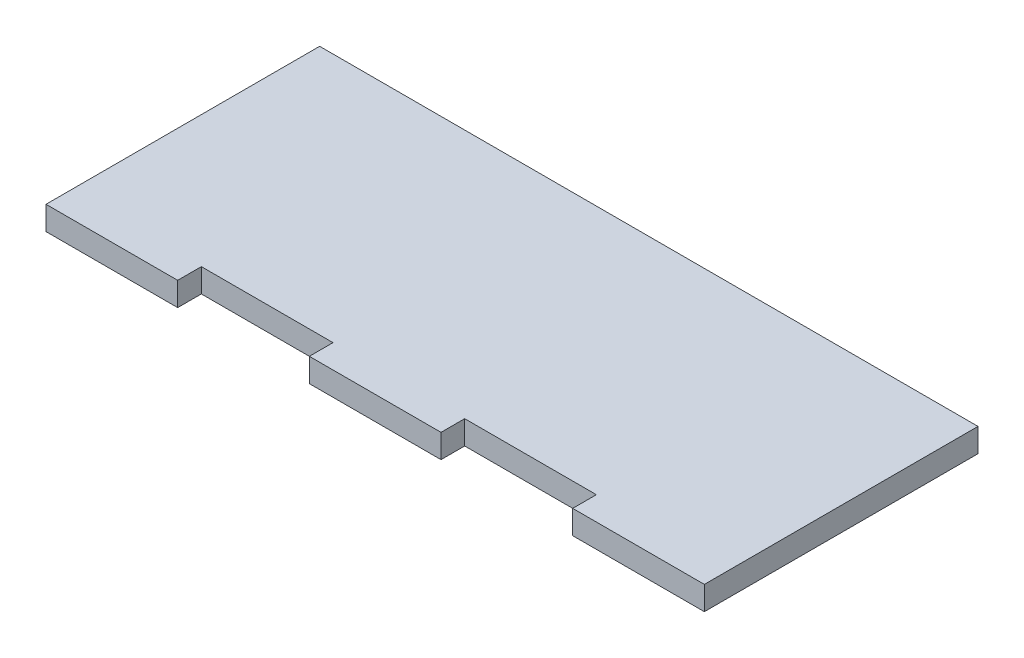
SolidWorks part; units mm, degrees
ref_plane "Front Plane" through (0, 0, 0) normal (0, 0, 1) x (1, 0, 0)
ref_plane "Top Plane" through (0, 0, 0) normal (0, 1, 0) x (1, 0, 0)
ref_plane "Right Plane" through (0, 0, 0) normal (1, 0, 0) x (0, 0, -1)
sketch "Sketch1" plane through (0, 0, 0) normal (0, 1, 0) x (1, 0, 0)
  line L1 (-69.721, 86.803) -> (130.8374, 86.803)
  line L2 (-69.721, 86.803) -> (-69.721, 3.4402)
  line L3 (-69.721, 3.4402) -> (130.8374, 3.4402)
  line L4 (130.8374, 86.803) -> (130.8374, 3.4402)
  dimension "D1" = 200.5584
  dimension "D2" = 83.3628
extrude "Boss-Extrude1" add sketch "Sketch1" along normal blind 7.2136
sketch "Sketch2" plane through (0, 0, 0) normal (0, -1, 0) x (1, 0, 0)
  line L0 (30.5582, -3.4402) -> (30.5582, -86.803) construction
  line L1 (-69.721, -3.4402) -> (130.8374, -3.4402) construction
  line L2 (130.8374, -86.803) -> (-69.721, -86.803) construction
  line L3 (90.7257, -10.6538) -> (50.614, -10.6538)
  line L4 (-69.721, -86.803) -> (-69.721, -3.4402) construction
  line L6 (50.614, -3.4402) -> (50.614, -10.6538)
  line L7 (-29.6093, -3.4402) -> (10.5024, -3.4402)
  line L8 (-29.6093, -3.4402) -> (-29.6093, -10.6538)
  line L9 (-29.6093, -10.6538) -> (10.5024, -10.6538)
  line L10 (10.5024, -3.4402) -> (10.5024, -10.6538)
  line L11 (90.7257, -3.4402) -> (50.614, -3.4402)
  line L12 (90.7257, -3.4402) -> (90.7257, -10.6538)
  dimension "D1" = 7.2136
  dimension "D2" = 40.1117
  dimension "D3" = 40.1117
extrude "Cut-Extrude1" cut sketch "Sketch2" against normal through all
equation "\"D1@Sketch1\"=\"Base Length@Assembled Container.Assembly\""
equation "\"D2@Sketch1\"=\"Side Height@Assembled Container.Assembly\""
equation "\"D1@Boss-Extrude1\"=\"Acrylic Thickness@Assembled Container.Assembly\""
equation "\"D1@Sketch2\"=\"Acrylic Thickness@Assembled Container.Assembly\""
equation "\"D2@Sketch2\"=\"Lid Long Side Outer Cutout@Assembled Container.Assembly\""
equation "\"D3@Sketch2\"=\"Lid Long Side Overhang@Assembled Container.Assembly\""
